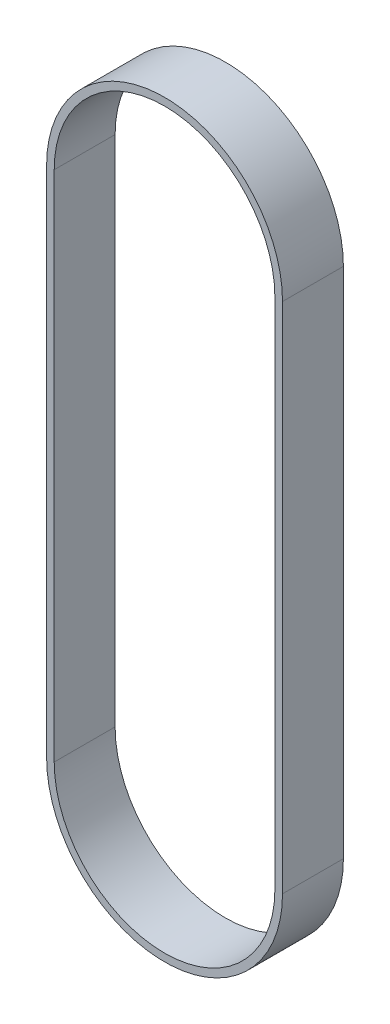
SolidWorks part; units mm, degrees
ref_plane "Front Plane" through (0, 0, 0) normal (0, 0, 1) x (1, 0, 0)
ref_plane "Top Plane" through (0, 0, 0) normal (0, 1, 0) x (1, 0, 0)
ref_plane "Right Plane" through (0, 0, 0) normal (1, 0, 0) x (0, 0, -1)
sketch "Sketch2" plane through (0, 0, 0) normal (0, 0, 1) x (1, 0, 0)
  line L0 (0, 0) -> (1, 0) construction
  line L1 (0, 0) -> (0, 1) construction
  line L2 (36.2419, 0) -> (36.2419, -168.4822)
  line L3 (-36.2419, -168.4822) -> (-36.2419, 0)
  arc A0 (-36.2419, 0) -> (36.2419, 0) centre (0, 0) cw
  arc A1 (36.2419, -168.4822) -> (-36.2419, -168.4822) centre (0, -168.4822) cw
extrude "Extrude-Thin1" add sketch "Sketch2" along normal blind 20 thin thin type one direction wall 2.5
